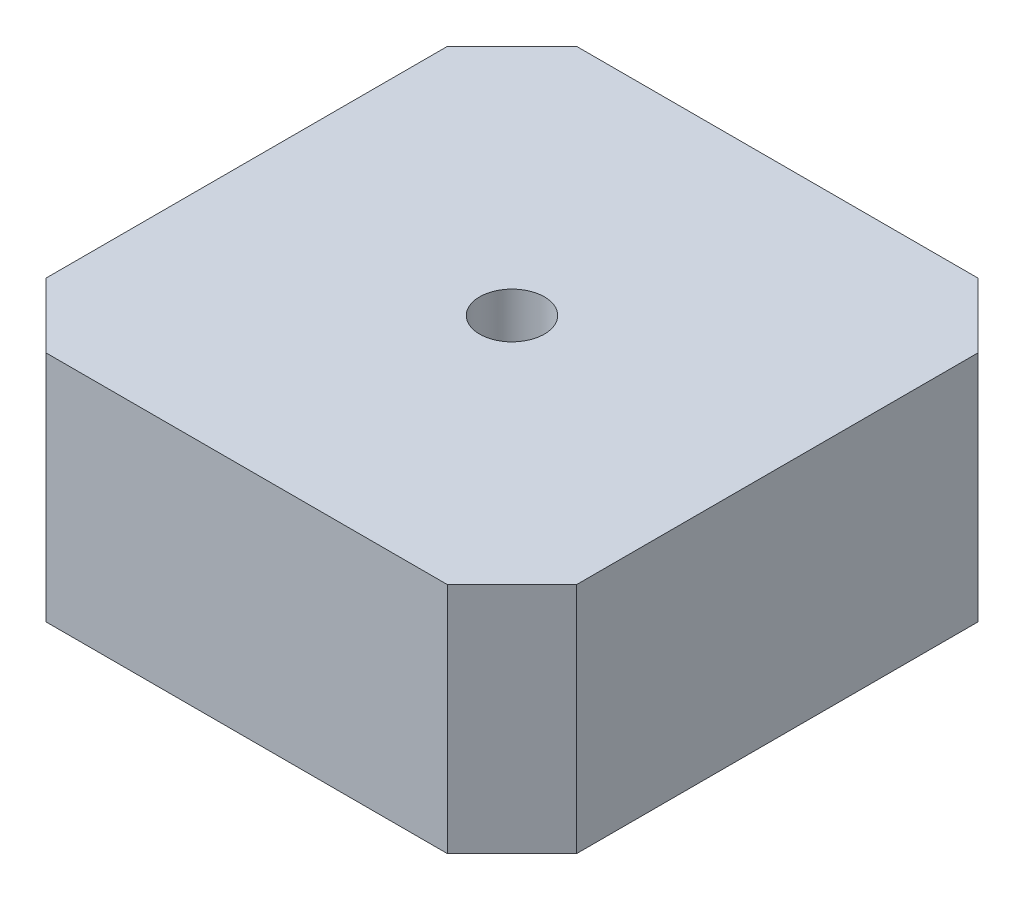
SolidWorks part; units mm, degrees
ref_plane "Front Plane" through (0, 0, 0) normal (0, 0, 1) x (1, 0, 0)
ref_plane "Top Plane" through (0, 0, 0) normal (0, 1, 0) x (1, 0, 0)
ref_plane "Right Plane" through (0, 0, 0) normal (1, 0, 0) x (0, 0, -1)
sketch "Sketch1" plane through (0, 0, 0) normal (0, 1, 0) x (1, 0, 0)
  line L0 (5, 0) -> (36, 0)
  line L1 (36, 0) -> (41, 5)
  line L2 (41, 5) -> (41, 36)
  line L3 (41, 36) -> (36, 41)
  line L4 (36, 41) -> (5, 41)
  line L5 (5, 41) -> (0, 36)
  line L6 (0, 36) -> (0, 5)
  line L7 (0, 5) -> (5, 0)
  circle A0 centre (20.5, 20.5) radius 2.5
  dimension "D8" = 5
  dimension "D1" = 31
  dimension "D2" = 31
  dimension "D3" = 31
  dimension "D4" = 5
  dimension "D5" = 5
  dimension "D6" = 5
  dimension "D7" = 5
extrude "Boss-Extrude1" add sketch "Sketch1" along normal blind 28
sketch "Sketch2" plane through (0, 28, 0) normal (0, 1, 0) x (1, 0, 0)
  line L1 (-2.1218, -5.7853) -> (43.9461, -5.7853)
  line L2 (-2.1218, -5.7853) -> (-2.1218, 48.5254)
  line L3 (-2.1218, 48.5254) -> (43.9461, 48.5254)
  line L4 (43.9461, -5.7853) -> (43.9461, 48.5254)
extrude "Cut-Extrude1" cut sketch "Sketch2" against normal blind 10
